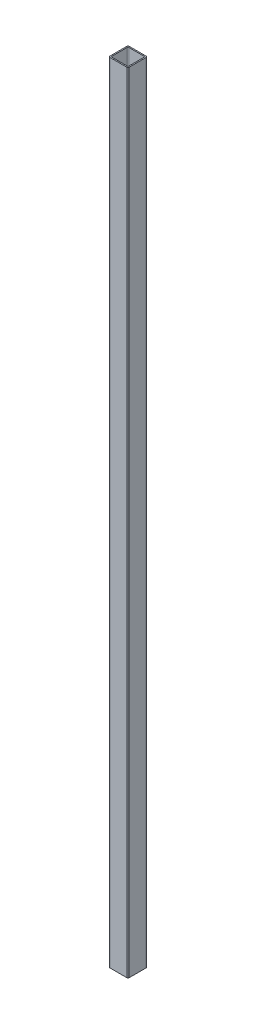
SolidWorks part; units mm, degrees
material "AISI 1020"
ref_plane "Спереди" through (0, 0, 0) normal (0, 0, 1) x (1, 0, 0)
ref_plane "Сверху" through (0, 0, 0) normal (0, 1, 0) x (1, 0, 0)
ref_plane "Справа" through (0, 0, 0) normal (1, 0, 0) x (0, 0, -1)
sketch "Эскиз1" plane through (0, 0, 0) normal (0, 1, 0) x (1, 0, 0)
  line L0 (0, 0) -> (492.5, 0) construction
  line B0 (3, 25) -> (47, 25)
  line B1 (0, 22) -> (0, -22)
  line B2 (3, -25) -> (47, -25)
  line B3 (50, 22) -> (50, -22)
  line B4 (5, 22) -> (45, 22)
  line B5 (3, 20) -> (3, -20)
  line B6 (5, -22) -> (45, -22)
  line B7 (47, 20) -> (47, -20)
  arc B8 (0, -22) -> (3, -25) centre (3, -22) ccw
  arc B9 (47, -25) -> (50, -22) centre (47, -22) ccw
  arc B10 (47, 25) -> (50, 22) centre (47, 22) cw
  arc B11 (3, 25) -> (0, 22) centre (3, 22) ccw
  arc B12 (3, -20) -> (5, -22) centre (5, -20) ccw
  arc B13 (45, -22) -> (47, -20) centre (45, -20) ccw
  arc B14 (45, 22) -> (47, 20) centre (45, 20) cw
  arc B15 (5, 22) -> (3, 20) centre (5, 20) ccw
sketch_block_instance "Труба профильная 50х50х3-1"
sketch_block "Труба профильная 50х50х3" parameters "D3"=3, "D4"=2, "D1"=50, "D2"=3
extrude "Бобышка-Вытянуть1" add sketch "Эскиз1" along normal up to surface (2045 mm away)
